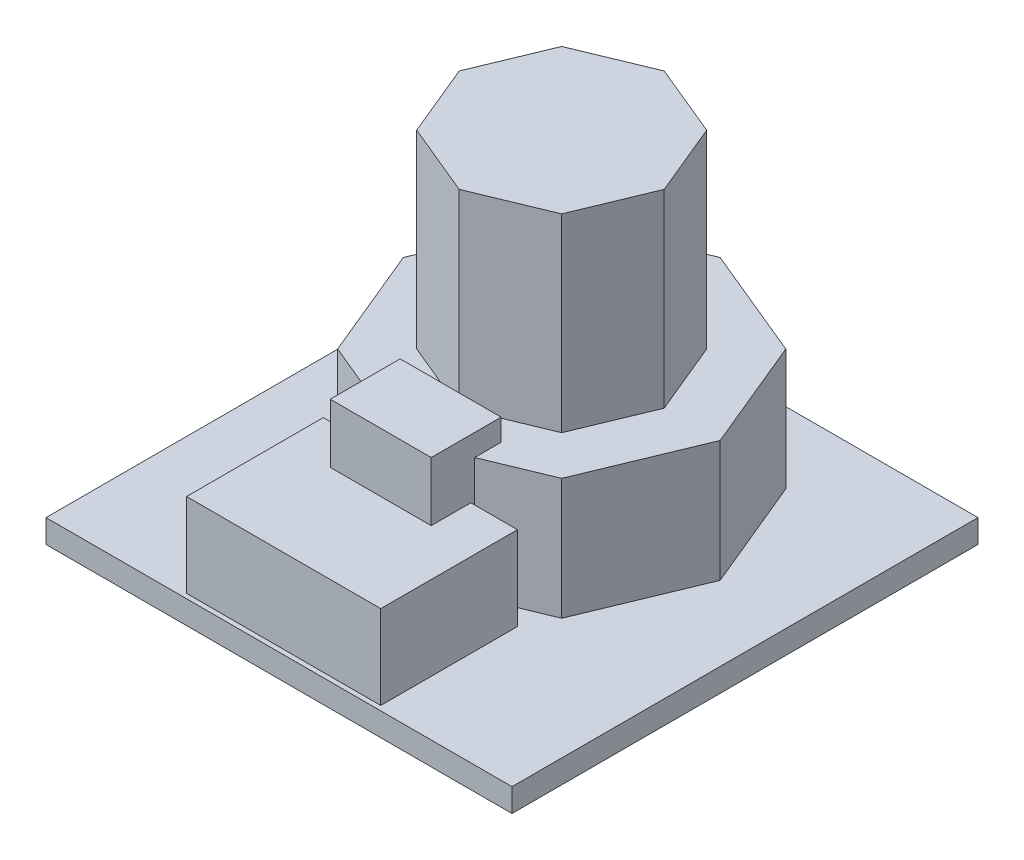
SolidWorks part; units mm, degrees
ref_plane "前视基准面" through (0, 0, 0) normal (0, 0, 1) x (1, 0, 0)
ref_plane "上视基准面" through (0, 0, 0) normal (0, 1, 0) x (1, 0, 0)
ref_plane "右视基准面" through (0, 0, 0) normal (1, 0, 0) x (0, 0, -1)
other "Configuration Table"
sketch "草图1" plane through (0, 0, 0) normal (0, 1, 0) x (1, 0, 0)
  line L1 (-150, -150) -> (150, -150)
  line L2 (-150, -150) -> (-150, 150)
  line L3 (-150, 150) -> (150, 150)
  line L4 (150, -150) -> (150, 150)
  line L5 (-150, -150) -> (150, 150) construction
  line L6 (-150, 150) -> (150, -150) construction
  point P0 (0, 0)
  dimension "D1" = 300
  dimension "D2" = 300
extrude "凸台-拉伸1" add sketch "草图1" against normal blind 15
sketch "草图2" plane through (0, 0, 0) normal (0, 1, 0) x (1, 0, 0)
  line L1 (102, 32) -> (72.1249, 104.1249)
  line L2 (72.1249, 104.1249) -> (0, 134)
  line L3 (0, 134) -> (-72.1249, 104.1249)
  line L4 (-72.1249, 104.1249) -> (-102, 32)
  line L5 (-102, 32) -> (-72.1249, -40.1249)
  line L6 (-72.1249, -40.1249) -> (0, -70)
  line L7 (0, -70) -> (72.1249, -40.1249)
  line L8 (72.1249, -40.1249) -> (102, 32)
  circle A0 centre (0, 32) radius 94.2357 construction
extrude "凸台-拉伸2" add sketch "草图2" along normal blind 78
sketch "草图3" plane through (0, 0, 0) normal (0, 1, 0) x (1, 0, 0)
  line L1 (66, 32) -> (46.669, 78.669)
  line L2 (46.669, 78.669) -> (0, 98)
  line L3 (0, 98) -> (-46.669, 78.669)
  line L4 (-46.669, 78.669) -> (-66, 32)
  line L5 (-66, 32) -> (-46.669, -14.669)
  line L6 (-46.669, -14.669) -> (0, -34)
  line L7 (0, -34) -> (46.669, -14.669)
  line L8 (46.669, -14.669) -> (66, 32)
  circle A0 centre (0, 32) radius 60.976 construction
extrude "凸台-拉伸3" add sketch "草图3" along normal blind 200
sketch "草图4" plane through (0, 0, 0) normal (0, 1, 0) x (1, 0, 0)
  line L1 (-62.5, -147) -> (62.5, -147)
  line L2 (-62.5, -147) -> (-62.5, -59)
  line L3 (-62.5, -59) -> (62.5, -59)
  line L4 (62.5, -147) -> (62.5, -59)
  line L5 (-62.5, -147) -> (62.5, -59) construction
  line L6 (-62.5, -59) -> (62.5, -147) construction
  point P0 (0, -103)
extrude "凸台-拉伸4" add sketch "草图4" along normal blind 54
sketch "草图5" plane through (0, 0, 0) normal (0, 1, 0) x (1, 0, 0)
  line L1 (-32.5, -84.5) -> (32.5, -84.5)
  line L2 (-32.5, -84.5) -> (-32.5, -39.5)
  line L3 (-32.5, -39.5) -> (32.5, -39.5)
  line L4 (32.5, -84.5) -> (32.5, -39.5)
  line L5 (-32.5, -84.5) -> (32.5, -39.5) construction
  line L6 (-32.5, -39.5) -> (32.5, -84.5) construction
  point P0 (0, -62)
extrude "凸台-拉伸5" add sketch "草图5" along normal blind 92
